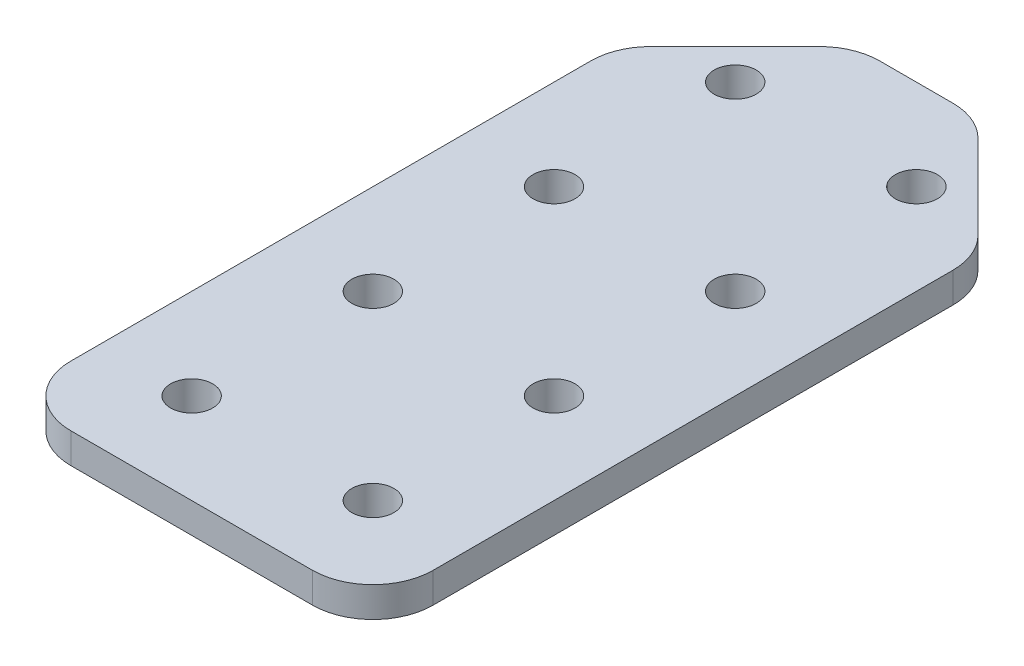
SolidWorks part; units mm, degrees
material "Acrylic (Medium-high impact)"
ref_plane "Front Plane" through (0, 0, 0) normal (0, 0, 1) x (1, 0, 0)
ref_plane "Top Plane" through (0, 0, 0) normal (0, 1, 0) x (1, 0, 0)
ref_plane "Right Plane" through (0, 0, 0) normal (1, 0, 0) x (0, 0, -1)
sketch "Sketch1" plane through (0, 0, 0) normal (0, 1, 0) x (1, 0, 0)
  line L1 (-38.1, -76.2) -> (38.1, -76.2)
  line L2 (-38.1, -76.2) -> (-38.1, 76.2)
  line L3 (-38.1, 76.2) -> (38.1, 76.2)
  line L4 (38.1, -76.2) -> (38.1, 76.2)
  line L5 (-38.1, -76.2) -> (38.1, 76.2) construction
  line L6 (-38.1, 76.2) -> (38.1, -76.2) construction
  point P0 (0, 0)
  dimension "D1" = 152.4
  dimension "D2" = 76.2
extrude "Boss-Extrude1" add sketch "Sketch1" along normal mid plane 6.35
sketch "Sketch2" plane through (0, 3.175, 0) normal (0, 1, 0) x (1, 0, 0)
  line L0 (38.1, 76.2) -> (-38.1, 76.2) construction
  line L1 (-38.1, 76.2) -> (-38.1, -76.2) construction
  line L2 (-19.05, 57.15) -> (-19.05, -57.15) construction
  circle A0 centre (-19.05, 57.15) radius 4.4196
  circle A1 centre (19.05, 57.15) radius 4.4196
  circle A2 centre (19.05, 19.05) radius 4.4196
  circle A3 centre (19.05, -19.05) radius 4.4196
  circle A4 centre (19.05, -57.15) radius 4.4196
  circle A5 centre (-19.05, 19.05) radius 4.4196
  circle A6 centre (-19.05, -19.05) radius 4.4196
  circle A7 centre (-19.05, -57.15) radius 4.4196
  point P6 (0, 0)
  point P7 (0, 0)
  point P8 (0, 0)
  point P23 (0, 0)
  point P24 (0, 0)
  point P25 (0, 0)
  point P26 (0, 0)
  point P28 (79.925, 42.8898)
  dimension "D3" = 8.8392
  dimension "D6" = 38.1
  dimension "D1" = 19.05
  dimension "D2" = 19.05
  dimension "D7" = 38.1
  dimension "D4" = 2
  dimension "D5" = 4
extrude "Cut-Extrude1" cut sketch "Sketch2" against normal through all
sketch "Sketch3" plane through (0, 3.175, 0) normal (0, 1, 0) x (1, 0, 0)
  line L0 (-38.1, 51.0553) -> (-12.9553, 76.2)
  line L1 (-38.1, 76.2) -> (-38.1, -76.2) construction
  line L2 (38.1, 76.2) -> (-38.1, 76.2) construction
  line L3 (-12.9553, 76.2) -> (-38.1, 76.2)
  line L4 (-38.1, 76.2) -> (-38.1, 51.0553)
  line L5 (12.9553, 76.2) -> (38.1, 76.2)
  line L6 (38.1, 76.2) -> (38.1, 51.0553)
  line L7 (38.1, -76.2) -> (38.1, 76.2) construction
  line L8 (38.1, 51.0553) -> (12.9553, 76.2)
  dimension "D1" = 45
  dimension "D2" = 45
  dimension "D3" = 17.78
extrude "Cut-Extrude2" cut sketch "Sketch3" against normal through all
fillet "Fillet1" radius 12.7 6 edges at (12.9553, 0, -76.2) (-38.1, 0, -51.0553) (-38.1, 0, 76.2) (38.1, 0, 76.2) (38.1, 0, -51.0553) (-12.9553, 0, -76.2)
